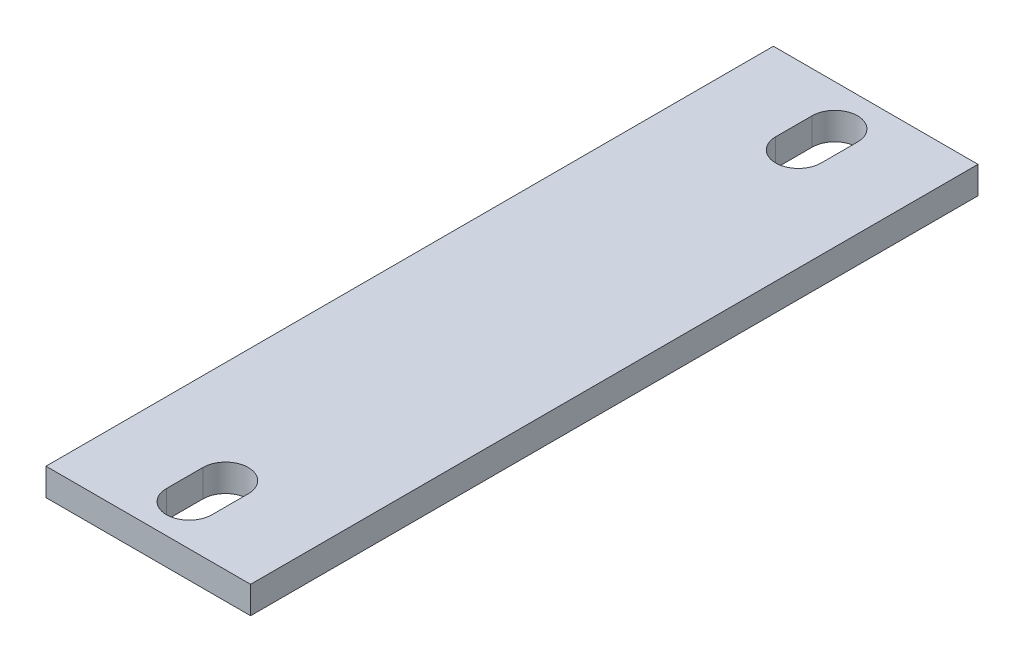
SolidWorks part; units mm, degrees
material "Сталь 08пс ГОСТ 535-88"
ref_plane "Спереди" through (0, 0, 0) normal (0, 0, 1) x (1, 0, 0)
ref_plane "Сверху" through (0, 0, 0) normal (0, 1, 0) x (1, 0, 0)
ref_plane "Справа" through (0, 0, 0) normal (1, 0, 0) x (0, 0, -1)
sketch "Эскиз1" plane through (0, 0, 0) normal (0, 0, 1) x (1, 0, 0)
  line L0 (-34.4035, 28.782) -> (34.4035, -28.782) construction
  line L1 (-34.4035, 28.782) -> (34.4035, 28.782)
  line L2 (-34.4035, 28.782) -> (-34.4035, -28.782)
  line L3 (-34.4035, -28.782) -> (34.4035, -28.782)
  line L4 (34.4035, 28.782) -> (34.4035, -28.782)
sketch "Эскиз2" plane through (0, 0, 0) normal (0, 1, 0) x (1, 0, 0)
  line L0 (0, 63) -> (0, 71) construction
  line L5 (-22.5, -80) -> (22.5, -80)
  line L6 (-22.5, -80) -> (-22.5, 80)
  line L7 (-22.5, 80) -> (22.5, 80)
  line L8 (22.5, -80) -> (22.5, 80)
  line L9 (0, 80) -> (0, -80) construction
  line L10 (-22.5, 0) -> (22.5, 0) construction
  line L11 (-5, 63) -> (-5, 71)
  line L12 (5, 63) -> (5, 71)
  line L13 (0, -63) -> (0, -71) construction
  line L14 (-5, -63) -> (-5, -71)
  line L15 (5, -63) -> (5, -71)
  arc A0 (-5, 63) -> (5, 63) centre (0, 63) ccw
  arc A1 (5, 71) -> (-5, 71) centre (0, 71) ccw
  arc A2 (-5, -63) -> (5, -63) centre (0, -63) cw
  arc A3 (5, -71) -> (-5, -71) centre (0, -71) cw
  point P0 (0, 0)
  point P7 (0, 67)
  point P14 (0, -67)
  dimension "D5" = 18
  dimension "D6" = 134
  dimension "D1" = 45
  dimension "D2" = 160
  dimension "D3" = 4
  dimension "D4" = 10
extrude "Бобышка-Вытянуть1" add sketch "Эскиз2" along normal mid plane 6
